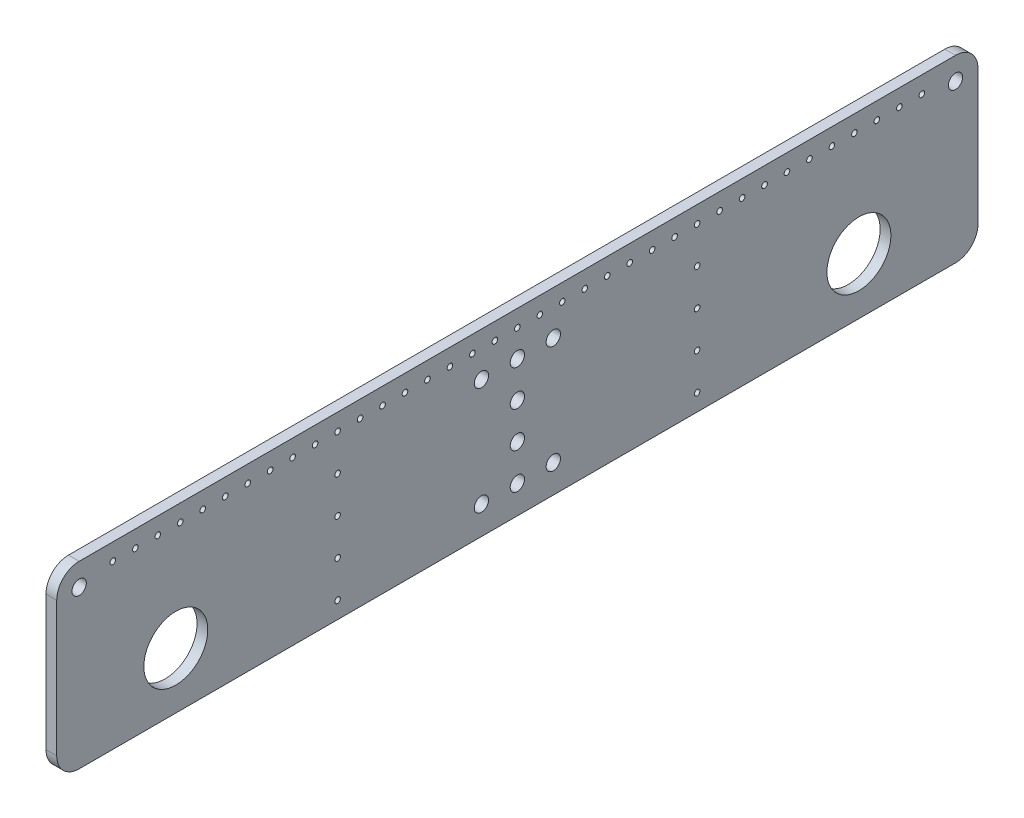
SolidWorks part; units mm, degrees
material "6061 Alloy"
ref_plane "Front Plane" through (0, 0, 0) normal (0, 0, 1) x (1, 0, 0)
ref_plane "Top Plane" through (0, 0, 0) normal (0, 1, 0) x (1, 0, 0)
ref_plane "Right Plane" through (0, 0, 0) normal (1, 0, 0) x (0, 0, -1)
sketch "Sketch2" plane through (0, 0, 0) normal (1, 0, 0) x (0, 0, -1)
  line L0 (-23.4813, 28.6683) -> (-23.4813, -31.3317)
  line L1 (-13.4813, 38.6683) -> (376.5187, 38.6683)
  line L2 (-13.4813, -41.3317) -> (376.5187, -41.3317)
  line L3 (386.5187, 28.6683) -> (386.5187, -31.3317)
  circle A1 centre (29.5187, -16.3317) radius 14.225
  circle A2 centre (333.5187, -16.3317) radius 14.225
  arc A15 (-23.4813, 28.6683) -> (-13.4813, 38.6683) centre (-13.4813, 28.6683) cw
  arc A16 (-13.4813, -41.3317) -> (-23.4813, -31.3317) centre (-13.4813, -31.3317) cw
  arc A17 (386.5187, 28.6683) -> (376.5187, 38.6683) centre (376.5187, 28.6683) ccw
  arc A18 (376.5187, -41.3317) -> (386.5187, -31.3317) centre (376.5187, -31.3317) ccw
  circle A59 centre (181.5187, -28.7717) radius 3.18
  circle A60 centre (197.5187, -28.7717) radius 3.18
  circle A63 centre (197.5187, 19.2283) radius 3.18
  circle A64 centre (181.5187, -12.7717) radius 3.18
  circle A65 centre (181.5187, 3.2283) radius 3.18
  circle A66 centre (181.5187, 19.2283) radius 3.18
  circle A67 centre (165.5187, -28.7717) radius 3.18
  circle A68 centre (165.5187, 19.2283) radius 3.18
  circle A69 centre (197.5187, -12.7717) radius 3.18 [skipped]
  circle A70 centre (197.5187, 3.2283) radius 3.18 [skipped]
  circle A152 centre (1.5187, 31.1683) radius 1.25
  circle A153 centre (11.5187, 31.1683) radius 1.25
  circle A154 centre (21.5187, 31.1683) radius 1.25
  circle A155 centre (31.5187, 31.1683) radius 1.25
  circle A156 centre (41.5187, 31.1683) radius 1.25
  circle A157 centre (51.5187, 31.1683) radius 1.25
  circle A158 centre (61.5187, 31.1683) radius 1.25
  circle A159 centre (71.5187, 31.1683) radius 1.25
  circle A160 centre (81.5187, 31.1683) radius 1.25
  circle A161 centre (91.5187, 31.1683) radius 1.25
  circle A162 centre (101.5187, 31.1683) radius 1.25
  circle A163 centre (111.5187, 31.1683) radius 1.25
  circle A164 centre (121.5187, 31.1683) radius 1.25
  circle A165 centre (131.5187, 31.1683) radius 1.25
  circle A166 centre (141.5187, 31.1683) radius 1.25
  circle A167 centre (151.5187, 31.1683) radius 1.25
  circle A168 centre (161.5187, 31.1683) radius 1.25
  circle A169 centre (171.5187, 31.1683) radius 1.25
  circle A170 centre (181.5187, 31.1683) radius 1.25
  circle A171 centre (191.5187, 31.1683) radius 1.25
  circle A172 centre (201.5187, 31.1683) radius 1.25
  circle A173 centre (211.5187, 31.1683) radius 1.25
  circle A174 centre (221.5187, 31.1683) radius 1.25
  circle A175 centre (231.5187, 31.1683) radius 1.25
  circle A176 centre (241.5187, 31.1683) radius 1.25
  circle A177 centre (251.5187, 31.1683) radius 1.25
  circle A178 centre (261.5187, 31.1683) radius 1.25
  circle A179 centre (271.5187, 31.1683) radius 1.25
  circle A180 centre (281.5187, 31.1683) radius 1.25
  circle A181 centre (291.5187, 31.1683) radius 1.25
  circle A182 centre (301.5187, 31.1683) radius 1.25
  circle A183 centre (311.5187, 31.1683) radius 1.25
  circle A184 centre (321.5187, 31.1683) radius 1.25
  circle A185 centre (331.5187, 31.1683) radius 1.25
  circle A186 centre (341.5187, 31.1683) radius 1.25
  circle A187 centre (351.5187, 31.1683) radius 1.25
  circle A188 centre (361.5187, 31.1683) radius 1.25
  circle A200 centre (101.5187, -33.8317) radius 1.25
  circle A216 centre (261.5187, -33.8317) radius 1.25
  circle A245 centre (-13.4813, 28.6683) radius 3.18
  circle A247 centre (376.5187, 28.6683) radius 3.18
  circle A267 centre (101.5187, -17.5817) radius 1.25
  circle A268 centre (261.5187, -17.5817) radius 1.25
  circle A269 centre (101.5187, -1.3317) radius 1.25
  circle A270 centre (261.5187, -1.3317) radius 1.25
  circle A271 centre (101.5187, 14.9183) radius 1.25
  circle A272 centre (261.5187, 14.9183) radius 1.25
  point P32 (-23.4813, 38.6683)
  point P35 (-23.4813, -41.3317)
  point P40 (386.5187, -41.3317)
  point P123 (181.5187, -41.3317)
  point P130 (0, 0)
  point P131 (0, 0)
  point P132 (0, 0)
  point P148 (0, 0)
  point P220 (304.518, -1.4618)
  point P273 (229.5187, -6.3017)
  point P278 (229.5187, 3.6983)
  point P301 (138.518, -1.1258)
  point P306 (128.7518, -1.5365)
  point P319 (53.5187, 3.6966)
  dimension "D3" = 25
  dimension "D7" = 10
  dimension "D8" = 10
  dimension "D9" = 6.36
  dimension "D10" = 7.5
  dimension "D11" = 23.75
  dimension "D13" = 12.56
  dimension "D20" = 4
  dimension "D23" = 2.5
  dimension "D21" = 40
  dimension "D26" = 400
  dimension "D31" = 10
  dimension "D6" = 25
  dimension "D5" = 2.5
  dimension "D22" = 56.25
  dimension "D12" = 10
  dimension "D18" = 25
  dimension "D19" = 35
  dimension "D32" = 285
  dimension "D14" = 28.45
  dimension "D1" = 80
  dimension "D2" = 410
  dimension "D4" = 53
  dimension "D24" = 72.5
  dimension "D25" = 357
  dimension "D27" = 189
  dimension "D28" = 205
  dimension "D29" = 221
  dimension "D30" = 125
  dimension "D34" = 28.56
  dimension "D35" = 44.56
  dimension "D36" = 60.56
  dimension "D15" = 2
  dimension "D16" = 4
  dimension "D17" = 2
extrude "Boss-Extrude1" add sketch "Sketch2" along normal blind 4.7625
